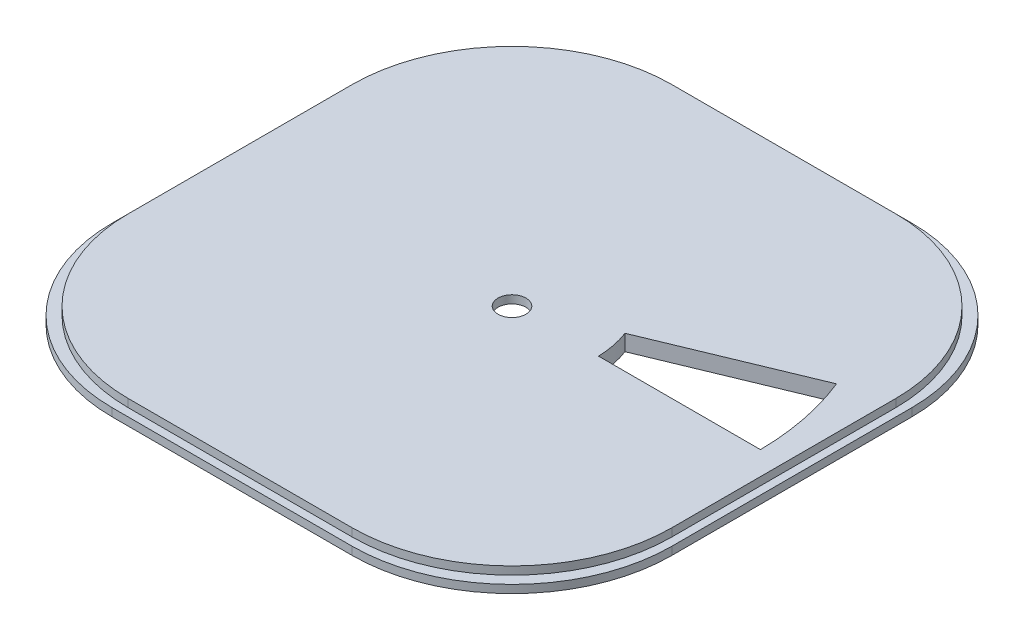
SolidWorks part; units mm, degrees
ref_plane "Front Plane" through (0, 0, 0) normal (0, 0, 1) x (1, 0, 0)
ref_plane "Top Plane" through (0, 0, 0) normal (0, 1, 0) x (1, 0, 0)
ref_plane "Right Plane" through (0, 0, 0) normal (1, 0, 0) x (0, 0, -1)
sketch "Sketch1" plane through (0, 0, 0) normal (0, 1, 0) x (1, 0, 0)
  line L1 (-30, 70) -> (30, 70)
  line L2 (-70, 30) -> (-70, -30)
  line L3 (-30, -70) -> (30, -70)
  line L4 (70, 30) -> (70, -30)
  line L5 (-28, 68) -> (28, 68)
  line L6 (-68, 28) -> (-68, -28)
  line L7 (-28, -68) -> (28, -68)
  line L8 (68, 28) -> (68, -28)
  arc A0 (-30, -70) -> (-70, -30) centre (-30, -30) cw
  arc A1 (30, -70) -> (70, -30) centre (30, -30) ccw
  arc A2 (70, 30) -> (30, 70) centre (30, 30) ccw
  arc A3 (-70, 30) -> (-30, 70) centre (-30, 30) cw
  arc A4 (-68, -28) -> (-28, -68) centre (-28, -28) ccw
  arc A5 (28, -68) -> (68, -28) centre (28, -28) ccw
  arc A6 (68, 28) -> (28, 68) centre (28, 28) ccw
  arc A7 (-68, 28) -> (-28, 68) centre (-28, 28) cw
  dimension "D1" = 40
  dimension "D2" = 40
extrude "Boss-Extrude5" add sketch "Sketch1" against normal blind 2 contours A3 L1 A2 L4 A1 L3 A0 L2
sketch "Sketch5" plane through (0, 0, 0) normal (0, 1, 0) x (1, 0, 0)
  line L1 (-28, 68) -> (28, 68)
  line L2 (-68, 28) -> (-68, -28)
  line L3 (-28, -68) -> (28, -68)
  line L4 (68, 28) -> (68, -28)
  arc A0 (-68, -28) -> (-28, -68) centre (-28, -28) ccw
  arc A1 (28, -68) -> (68, -28) centre (28, -28) ccw
  arc A2 (68, 28) -> (28, 68) centre (28, 28) ccw
  arc A3 (-68, 28) -> (-28, 68) centre (-28, 28) cw
  dimension "D1" = 40
extrude "Boss-Extrude6" add sketch "Sketch5" along normal blind 2
sketch "Sketch6" plane through (0, -2, 0) normal (0, -1, 0) x (1, 0, 0)
  circle A0 centre (0, 0) radius 11
extrude "Cut-Extrude1" cut sketch "Sketch6" against normal blind 2
sketch "Sketch7" plane through (0, 0, 0) normal (0, -1, 0) x (1, 0, 0)
  circle A0 centre (0, 0) radius 2.6037
extrude "Cut-Extrude3" cut sketch "Sketch7" against normal blind 35 and the other way blind 24 contours A0
sketch "Sketch8" plane through (0, 0, 0) normal (0, 1, 0) x (1, 0, 0)
  circle A0 centre (13, 13) radius 1.4
  circle A1 centre (13, -13) radius 1.4
  circle A2 centre (-13, -13) radius 1.4
  circle A3 centre (-13, 13) radius 1.4
extrude "Boss-Extrude8" add sketch "Sketch8" against normal blind 4
sketch "Sketch15" plane through (0, 2, 0) normal (0, 1, 0) x (1, 0, 0)
  line L0 (20.0029, 8.2609) -> (57.4252, 23.7618)
  line L1 (21.6471, -0.0048) -> (62.1527, -0.0048)
  arc A0 (21.6471, -0.0048) -> (20.0029, 8.2609) centre (-3.3438, -0.6794) ccw
  arc A1 (62.1527, -0.0048) -> (57.4252, 23.7618) centre (-3.3438, -0.6794) ccw
extrude "Cut-Extrude8" cut sketch "Sketch15" against normal blind 4
sketch "Sketch17" plane through (0, -4, 0) normal (0, -1, 0) x (1, 0, 0)
  circle A4 centre (13, 13) radius 1.4
  circle A5 centre (13, -13) radius 1.4
  circle A6 centre (-13, -13) radius 1.4
  circle A7 centre (-13, 13) radius 1.4
extrude "Cut-Extrude9" cut sketch "Sketch17" against normal blind 2
sketch "Sketch18" plane through (0, -2, 0) normal (0, -1, 0) x (1, 0, 0)
  line L1 (-70, -30) -> (-70, 30) construction
  line L2 (-70, 0) -> (-70, 4)
  line L3 (-70, 4) -> (-10.247, 4)
  line L4 (-70, 0) -> (-70, -4)
  line L5 (-70, -4) -> (-10.247, -4)
  circle A0 centre (0, 0) radius 11 construction
  circle A1 centre (0, 0) radius 11 construction
  arc A2 (-10.247, 4) -> (-10.247, -4) centre (0, 0) ccw
extrude "Cut-Extrude10" cut sketch "Sketch18" against normal blind 1
sketch "Sketch19" plane through (0, 0, 0) normal (0, -1, 0) x (1, 0, 0)
  circle A0 centre (0, 0) radius 3.5
extrude "Cut-Extrude11" cut sketch "Sketch19" against normal blind 10
